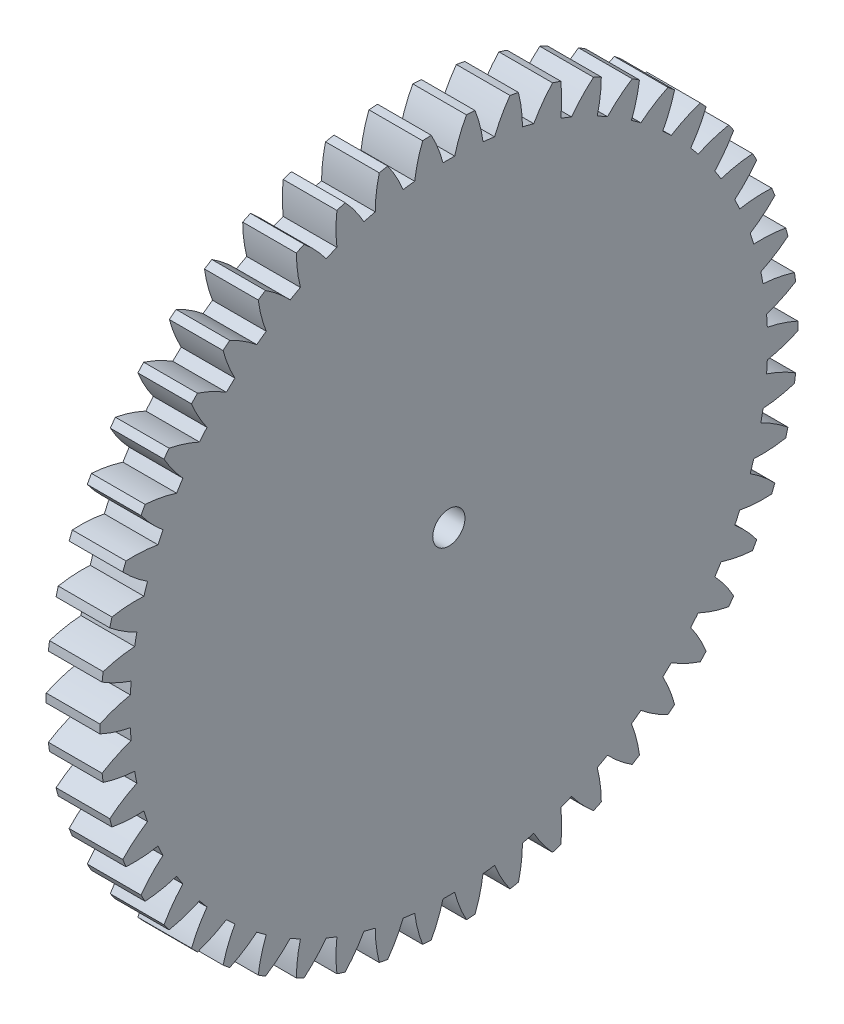
SolidWorks part; units mm, degrees
ref_plane "Plane1" through (0, 0, 0) normal (0, 0, 1) x (1, 0, 0)
ref_plane "Plane2" through (0, 0, 0) normal (0, 1, 0) x (1, 0, 0)
ref_plane "Plane3" through (0, 0, 0) normal (1, 0, 0) x (0, 0, -1)
other "Configuration Table"
sketch "HoldingSke" plane through (0, 0, 0) normal (0, 1, 0) x (1, 0, 0)
  line L0 (0, 0) -> (0.5142, -0.6128)
  line L1 (-15, 0) -> (100, 0) construction
  line L2 (0, 0) -> (-2.1039, 2.3779)
  line L3 (0, 0) -> (-11.863, 4.5341)
  line L4 (0, 0) -> (5.5511, 6.6156)
  line L5 (0, 0) -> (-46.8476, -17.4728)
  line L6 (0, 0) -> (-4.1448, -2.7965)
  line L7 (-2.1039, 2.3779) -> (8.6586, 51.2059)
  line L8 (-76.2, 54.61) -> (-75.7, 54.61)
  line L9 (-71.009, 38.7566) -> (-53.1078, 45.2721)
  line L10 (-76.2, 71.12) -> (104.1128, 71.12)
  line L11 (0, 0) -> (-5, 0)
  line L12 (-76.2, 101.6) -> (-76.155, 101.6)
  line L13 (24.9733, 27.94) -> (52.9518, 28.4284)
  line L14 (24.9733, 27.94) -> (24.9743, 27.94)
  line L15 (24.9733, 27.94) -> (100.4006, 29.5858)
  line L16 (-63.627, -1.25) -> (-12.827, -1.25)
  circle A0 centre (0, 0) radius 1.5
  circle A1 centre (0, 0) radius 29.6865
  circle A2 centre (0, 0) radius 37.5
  circle A3 centre (0, 0) radius 1.5
  dimension "MHD" = 59.373
  dimension "Hub_dia" = 75
  dimension "Bore" = 3
  dimension "MBD" = 3
  dimension "Num_teeth" = 50
  dimension "Pitch" = 0.8
  dimension "Overall_len" = 50
  dimension "Show_teeth" = 50
  dimension "Thickness" = 5
  dimension "OAL" = 50.0001
  dimension "T_dim" = 0.5
  dimension "Ap" = 20
  dimension "H" = 19.05
  dimension "Pitch_radius" = 180.3128
  dimension "Width" = 5
  dimension "Backlash" = 0.045
  dimension "Addendum_fac" = 1
  dimension "Dedendum_fac" = 1.25
  dimension "Clearance_fac" = 0.25
  dimension "Dedendum_add" = 0.001
  dimension "Module" = 1.25
sketch "BasProSke" plane through (0, 0, 0) normal (0, 1, 0) x (1, 0, 0)
  line L0 (-10, 0) -> (60, 0) construction
  line L1 (0, 0) -> (0, 32.5)
  line L2 (0, 0) -> (5, 0)
  line L3 (5, 0) -> (5, 32.5)
  line L4 (5, 32.5) -> (0, 32.5)
  dimension "Thickness" = 5
  dimension "Diameter" = 65
revolve "Base-Revolve" add sketch "BasProSke" angle 360 about L0
sketch "TooCutSke" plane through (0, 0, 0) normal (1, 0, 0) x (0, 0, -1)
  line L1 (0, 0) -> (0, 107) construction
  line L2 (0, 0) -> (-1.0603, 31.232) construction
  line L3 (0, 0) -> (-3.9228, 62.3506) construction
  line L4 (-1.0603, 31.232) -> (-1.9614, 31.1753) construction
  arc A0 (0.543, 29.6815) -> (-0.543, 29.6815) centre (0, 0) ccw
  arc A1 (1.6539, 32.4833) -> (-1.6539, 32.4833) centre (0, 0) ccw
  circle A2 centre (0, 0) radius 31.25 construction
  circle A3 centre (0, 0) radius 29.3654 construction
  arc A4 (-0.543, 29.6815) -> (-1.6539, 32.4833) centre (-12.6336, 26.5088) ccw
  arc A5 (1.6539, 32.4833) -> (0.543, 29.6815) centre (12.6336, 26.5088) ccw
  dimension "Root_dia" = 59.373
  dimension "Overcut_dia" = 65.0508
  dimension "Pitch_dia" = 62.5
  dimension "Base_dia" = 58.7308
  dimension "Flank_rad" = 12.5
  dimension "Half_ang" = 3.6
  dimension "Half_CT" = 0.9028
extrude "ToothCut" cut sketch "TooCutSke" along normal through all
fillet "Breaks" [suppressed] radius 0.025
fillet "RootFillets" [suppressed] radius 0.3135
pattern_circular "TeethCuts" count 50 every 7.2 about axis through (-10, 0, 0) along (1, 0, 0) of "ToothCut", "RootFillets", "Breaks"
sketch "HubNeaOneSke" plane through (0, 0, 0) normal (-1, 0, 0) x (0, 0, 1)
  circle A0 centre (0, 0) radius 29.6865
  dimension "Diameter" = 59.373
extrude "HubNearOne" [suppressed] add sketch "HubNeaOneSke" along normal blind 45.0001
sketch "HubNeaBotSke" plane through (0, 0, 0) normal (-1, 0, 0) x (0, 0, 1)
  circle A0 centre (0, 0) radius 29.6865
  dimension "Diameter" = 59.373
extrude "HubNearBoth" [suppressed] add sketch "HubNeaBotSke" along normal blind 22.5
ref_plane "FarPln" through (5, 0, 0) normal (1, 0, 0) x (0, 0, -1)
sketch "HubFarSke" plane through (5, 0, 0) normal (1, 0, 0) x (0, 0, -1)
  circle A0 centre (0, 0) radius 29.6865
  dimension "Diameter" = 59.373
extrude "HubFar" [suppressed] add sketch "HubFarSke" along normal blind 22.5
sketch "BorSke" plane through (0, 0, 0) normal (1, 0, 0) x (0, 0, -1)
  circle A0 centre (0, 0) radius 1.5
  dimension "Diameter" = 3
extrude "Bore" cut sketch "BorSke" along normal mid plane 100.0001
sketch "KeySke" plane through (0, 0, 0) normal (1, 0, 0) x (0, 0, -1)
  line L0 (-0.6, 0) -> (-0.6, 2)
  line L1 (-0.6, 2) -> (0.6, 2)
  line L2 (0.6, 2) -> (0.6, 0)
  line L3 (0, 0) -> (0, 34) construction
  line L4 (-0.6, 0) -> (0.6, 0)
  dimension "Offset" = 2
  dimension "Width" = 1.2
extrude "Keyway" [suppressed] cut sketch "KeySke" along normal mid plane 100.0001
pattern_circular "Keyway2" [suppressed] count 2 every 90 about axis through (-10, 0, 0) along (1, 0, 0)
equation "' \"Module@HoldingSke\" = 6.35"
equation "' \"Num_teeth@HoldingSke\" = 12"
equation "' \"Ap@HoldingSke\" =  20"
equation "' \"Ap@HoldingSke\" = 20"
equation "' \"Width@HoldingSke\" = 0.5 * 25.4"
equation "' \"Hub_dia@HoldingSke\"= 1 * 25.4"
equation "' \"Hub_dia@HoldingSke\" = 1 * 25.4"
equation "' \"Overall_len@HoldingSke\" = 1.0 * 25.4"
equation "' \"Bore@HoldingSke\" = 0.75 * 25.4"
equation "' \"T_dim@HoldingSke\" = 0.1 * 25.4"
equation "' \"Width@KeySke\" = 0.25 * 25.4"
equation "' \"Show_teeth@HoldingSke\" = 13"
equation "' \"Backlash@HoldingSke\" = 0.009 * 25.4"
equation "' \"Addendum_fac@HoldingSke\" = 1.0"
equation "' \"Dedendum_fac@HoldingSke\" = 1.25"
equation "' \"Dedendum_add@HoldingSke\" = 0.00005 * 25.4"
equation "' \"Clearance_fac@HoldingSke\" = 0.25"
equation "\"Pitch@HoldingSke\" = 1 / \"Module@HoldingSke\""
equation "\"Overcut_dia@TooCutSke\" = (\"Num_teeth@HoldingSke\" + 2 * \"Addendum_fac@HoldingSke\") / \"Pitch@HoldingSke\" + 0.002 * 25.4"
equation "\"Pitch_dia@TooCutSke\" = \"Num_teeth@HoldingSke\" / \"Pitch@HoldingSke\""
equation "\"Base_dia@TooCutSke\" = \"Num_teeth@HoldingSke\" / \"Pitch@HoldingSke\" * cos((\"Ap@HoldingSke\"  * 3.14159265 / 180))"
equation "\"Root_dia@TooCutSke\" = (\"Num_teeth@HoldingSke\" + 2) / \"Pitch@HoldingSke\" - 2 * (\"Addendum_fac@HoldingSke\" + \"Dedendum_fac@HoldingSke\") / \"Pitch@HoldingSke\" - \"Dedendum_add@HoldingSke\" * 2"
equation "\"Half_ang@TooCutSke\" = 180 / \"Num_teeth@HoldingSke\""
equation "\"Half_CT@TooCutSke\" = \"Num_teeth@HoldingSke\" / \"Pitch@HoldingSke\" * sin((3.14159265 / 2 / \"Num_teeth@HoldingSke\")) / 2 - 7 * \"Backlash@HoldingSke\" / 4"
equation "\"Flank_rad@TooCutSke\" = \"Num_teeth@HoldingSke\" / \"Pitch@HoldingSke\" / 5"
equation "\"Radius@RootFillets\" = \"Clearance_fac@HoldingSke\" / \"Pitch@HoldingSke\" + \"Dedendum_add@HoldingSke\""
equation "\"Break_rad@Breaks\" = 0.02 / \"Pitch@HoldingSke\""
equation "\"Thickness@HoldingSke\" = \"Width@HoldingSke\""
equation "\"OAL@HoldingSke\" = \"Thickness@HoldingSke\""
equation "\"MHD@HoldingSke\" = (\"Num_teeth@HoldingSke\" + 2) / \"Pitch@HoldingSke\" - 2 * (\"Addendum_fac@HoldingSke\" + \"Dedendum_fac@HoldingSke\")  / \"Pitch@HoldingSke\" - \"Dedendum_add@HoldingSke\" * 2"
equation "\"MBD@HoldingSke\" = (\"Num_teeth@HoldingSke\" + 2) / \"Pitch@HoldingSke\" - 2 * (\"Addendum_fac@HoldingSke\" + \"Dedendum_fac@HoldingSke\")  / \"Pitch@HoldingSke\" - \"Dedendum_add@HoldingSke\" * 2 - 0.002 * 25.4"
equation "\"MHD@HoldingSke\" = ((sgn( \"MHD@HoldingSke\" - \"Hub_dia@HoldingSke\" )-1)*( \"MHD@HoldingSke\" - \"Hub_dia@HoldingSke\" ))/-2+ \"Hub_dia@HoldingSke\""
equation "\"MBD@HoldingSke\" = ((sgn( \"MBD@HoldingSke\" - \"Bore@HoldingSke\" )-1)*( \"MBD@HoldingSke\" - \"Bore@HoldingSke\" ))/-2+ \"Bore@HoldingSke\""
equation "\"OAL@HoldingSke\" = ((sgn( \"OAL@HoldingSke\" - \"Overall_len@HoldingSke\" )+1)*( \"OAL@HoldingSke\" - \"Overall_len@HoldingSke\" ))/2 + \"Overall_len@HoldingSke\" + 0.000002 * 25.4"
equation "\"Num_teeth@TeethCuts\" = int( \"Show_teeth@HoldingSke\" ) + 1"
equation "\"Num_teeth@TeethCuts\" = ((sgn( \"Num_teeth@TeethCuts\" - \"Num_teeth@HoldingSke\" )-1)*( \"Num_teeth@TeethCuts\" - \"Num_teeth@HoldingSke\" ))/-2+ \"Num_teeth@HoldingSke\""
equation "\"Num_teeth@TeethCuts\" = ((sgn( \"Num_teeth@TeethCuts\" - 2.0)+1)*( \"Num_teeth@TeethCuts\" - 2.0))/2 +2.0"
equation "\"Angle@TeethCuts\" = 360.0 / \"Num_teeth@HoldingSke\""
equation "\"Diameter@BasProSke\" = (\"Num_teeth@HoldingSke\" + 2 * \"Addendum_fac@HoldingSke\") / \"Pitch@HoldingSke\""
equation "\"Thickness@BasProSke\"  = \"Thickness@HoldingSke\""
equation "' \"Fillet_rad@BasProSke\" =  \"Thickness@HoldingSke\" * 0.05"
equation "' \"Fillet_rad@BasProSke\" = \"Thickness@HoldingSke\" * 0.05"
equation "\"MHD@HoldingSke\" = ((sgn( \"MHD@HoldingSke\" - \"Root_dia@TooCutSke\" )-1)*( \"MHD@HoldingSke\" - \"Root_dia@TooCutSke\" ))/-2+ \"Root_dia@TooCutSke\""
equation "\"Diameter@HubNeaOneSke\" = \"MHD@HoldingSke\""
equation "\"Length@HubNearOne\" = \"OAL@HoldingSke\" - \"Thickness@BasProSke\""
equation "\"Diameter@HubNeaBotSke\" = \"MHD@HoldingSke\""
equation "\"Length@HubNearBoth\" = ( \"OAL@HoldingSke\" - \"Thickness@BasProSke\" ) / 2.0"
equation "\"Thickness@FarPln\" = \"Thickness@BasProSke\""
equation "\"Diameter@HubFarSke\" = \"MHD@HoldingSke\""
equation "\"Length@HubFar\" = ( \"OAL@HoldingSke\" - \"Thickness@BasProSke\" ) / 2.0"
equation "\"Diameter@BorSke\" = \"MBD@HoldingSke\""
equation "\"D1@Bore\" = \"OAL@HoldingSke\" * 2.0"
equation "\"D1@Keyway\" = \"OAL@HoldingSke\" * 2.0"
equation "\"Offset@KeySke\" = \"T_dim@HoldingSke\" + \"MBD@HoldingSke\" / 2.0"
